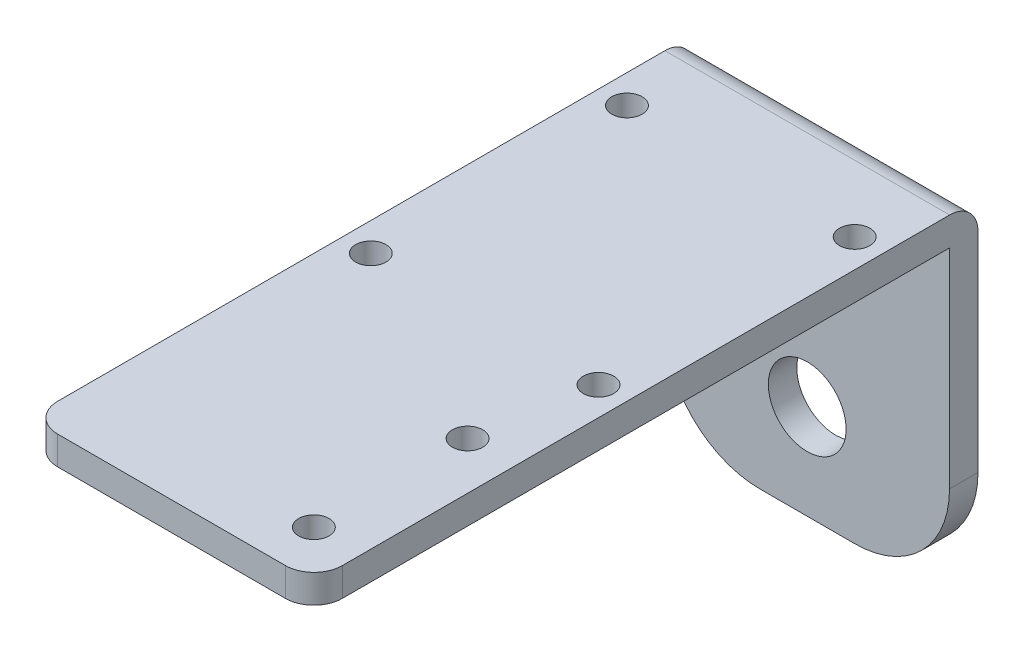
SolidWorks part; units mm, degrees
ref_plane "前视基准面" through (0, 0, 0) normal (0, 0, 1) x (1, 0, 0)
ref_plane "上视基准面" through (0, 0, 0) normal (0, 1, 0) x (1, 0, 0)
ref_plane "右视基准面" through (0, 0, 0) normal (1, 0, 0) x (0, 0, -1)
other "Configuration Table"
sketch "草图1" plane through (0, 0, 0) normal (0, 1, 0) x (1, 0, 0)
  line L1 (-15, 35) -> (15, 35)
  line L2 (-15, 35) -> (-15, -35)
  line L3 (-15, -35) -> (15, -35)
  line L4 (15, 35) -> (15, -35)
  line L5 (-15, 35) -> (15, -35) construction
  line L6 (-15, -35) -> (15, 35) construction
  circle A0 centre (-12, 25) radius 1.6
  circle A1 centre (12, 25) radius 1.6
  circle A2 centre (12, -2) radius 1.6
  circle A3 centre (-12, -2) radius 1.6
  circle A4 centre (10, -30) radius 1.6
  circle A5 centre (10, -13.8) radius 1.6
  point P0 (0, 0)
  dimension "D3" = 3.2
  dimension "D5" = 3
  dimension "D8" = 24
  dimension "D9" = 27
  dimension "D10" = 3.2
  dimension "D11" = 5
  dimension "D12" = 5
  dimension "D14" = 16.2
  dimension "D1" = 70
  dimension "D2" = 30
  dimension "D4" = 10
  dimension "D6" = 2
  dimension "D7" = 2
  dimension "D13" = 2
extrude "凸台-拉伸1" add sketch "草图1" along normal blind 3
sketch "草图2" plane through (0, 0, 0) normal (0, -1, 0) x (1, 0, 0)
  line L0 (-15, -35) -> (-15, 35) construction
  line L1 (15, -35) -> (-15, -35)
  line L2 (15, -35) -> (15, -32)
  line L3 (15, -32) -> (-15, -32)
  line L4 (-15, -35) -> (-15, -32)
  dimension "D1" = 3
  dimension "D2" = 30
extrude "凸台-拉伸2" add sketch "草图2" along normal blind 32
sketch "草图3" plane through (0, 0, -35) normal (0, 0, -1) x (-1, 0, 0)
  line L1 (0, 3) -> (0, -32) construction
  line L2 (-15, 3) -> (15, 3) construction
  line L3 (15, -32) -> (-15, -32) construction
  line L4 (-15, 3) -> (-15, -32) construction
  circle A1 centre (0, -22) radius 4.1
  dimension "D1" = 8.2
  dimension "D2" = 15
  dimension "D3" = 10
extrude "切除-拉伸1" cut sketch "草图3" against normal up to next
fillet "圆角1" radius 3 3 edges at (-15, 1.5, 35) (15, 1.5, 35) (0, 3, -35)
fillet "圆角2" radius 10 2 edges at (-15, -32, -33.5) (15, -32, -33.5)
